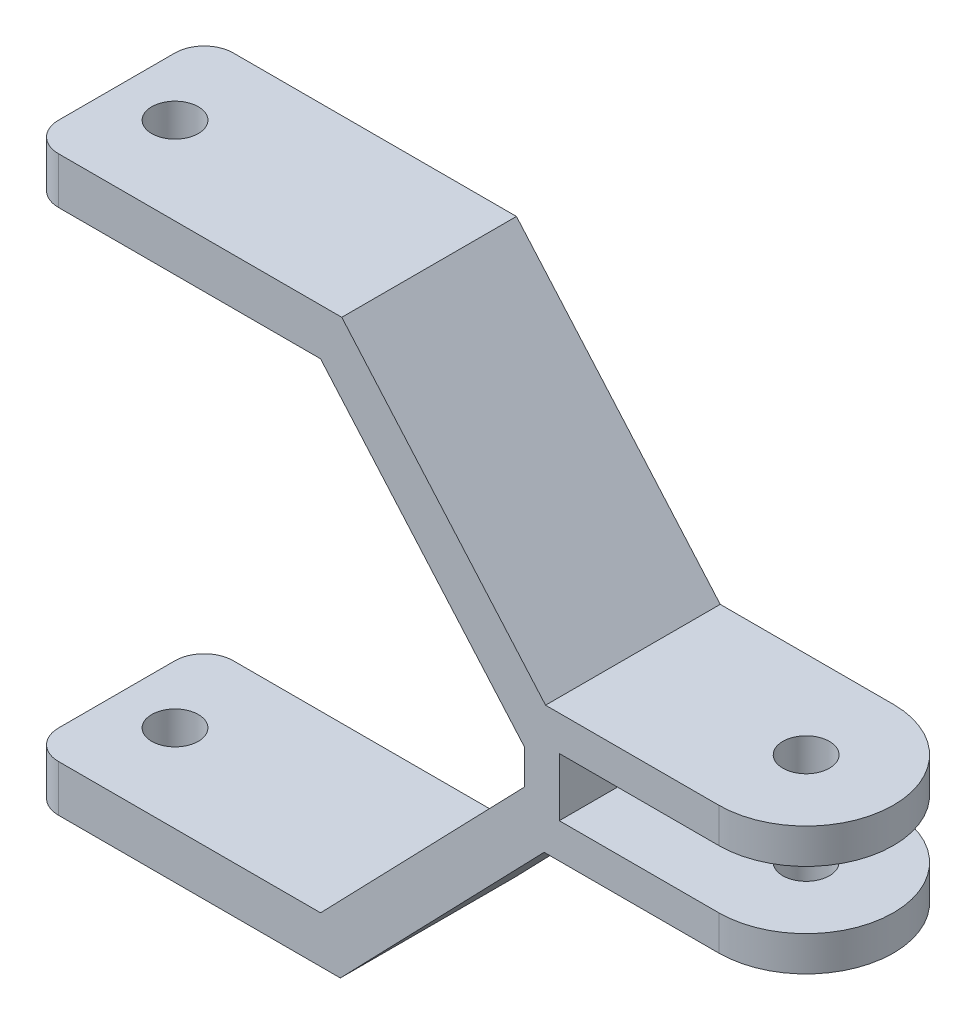
SolidWorks part; units mm, degrees
ref_plane "前基準面" through (0, 0, 0) normal (0, 0, 1) x (1, 0, 0)
ref_plane "上基準面" through (0, 0, 0) normal (0, 1, 0) x (1, 0, 0)
ref_plane "右基準面" through (0, 0, 0) normal (1, 0, 0) x (0, 0, -1)
sketch "草圖1" plane through (0, 0, 0) normal (0, 0, 1) x (1, 0, 0)
  line L0 (-26.6965, 45.2) -> (-47.6965, 45.2)
  line L1 (-25, 0) -> (-51.6965, 0)
  line L2 (7.5, 18.1) -> (7.5, 21.1)
  line L3 (-24.8754, 49.2) -> (-51.6965, 49.2)
  line L4 (-51.6965, 0) -> (-51.6965, 4)
  line L5 (-24.8754, 49.2) -> (-7.3754, 29.1)
  line L6 (-7.5, 18.1) -> (-25, 0)
  line L7 (-7.3754, 29.1) -> (7.5, 29.1)
  line L8 (-7.5, 18.1) -> (7.5, 18.1)
  line L9 (7.5, 26.1) -> (7.5, 29.1)
  line L10 (-26.6965, 4) -> (-47.6965, 4)
  line L11 (-9.1965, 22.1) -> (-26.6965, 4)
  line L12 (-47.6965, 45.2) -> (-51.6965, 45.2)
  line L13 (7.5, 26.1) -> (-6.1965, 26.1)
  line L14 (-51.6965, 4) -> (-47.6965, 4)
  line L15 (-26.6965, 45.2) -> (-9.1965, 25.1)
  line L16 (-9.1965, 25.1) -> (-9.1965, 22.1)
  line L17 (-51.6965, 45.2) -> (-51.6965, 49.2)
  line L18 (-9.1965, 22.1) -> (3.5, 22.1) construction
  line L19 (-9.1965, 25.1) -> (3.5, 25.1) construction
  line L20 (3.5, 22.1) -> (3.5, 25.1) construction
  line L21 (-47.6965, 4) -> (-47.6965, 45.2) construction
  line L22 (-51.6965, 0) -> (-51.6965, 49.2) construction
  line L24 (7.5, 21.1) -> (-6.1965, 21.1)
  line L25 (-6.1965, 26.1) -> (-6.1965, 21.1)
  line L26 (7.5, 18.1) -> (7.5, 29.1) construction
  dimension "D4" = 25
  dimension "D5" = 15
  dimension "D1" = 41.2
  dimension "D2" = 4
  dimension "D3" = 17.5
  dimension "D7" = 3
  dimension "D8" = 3
  dimension "D9" = 3
extrude "填料-伸長1" add sketch "草圖1" along normal blind 15
sketch "草圖2" plane through (0, 0, 0) normal (0, -1, 0) x (1, 0, 0)
  line L0 (-51.6965, 15) -> (-51.6965, 0) construction
  line L1 (-51.6965, 15) -> (-25, 15) construction
  circle A0 centre (-46.6965, 7.5) radius 2
  dimension "D1" = 5
  dimension "D2" = 7.5
  dimension "D3" = 4
extrude "除料-伸長1" cut sketch "草圖2" against normal up to surface (49.2 mm away) up to face at (-38.286, 49.2, 7.5)
sketch "草圖3" plane through (0, 18.1, 0) normal (0, -1, 0) x (1, 0, 0)
  line L0 (7.5, 15) -> (7.5, 0) construction
  circle A0 centre (7.5, 7.5) radius 7.5
extrude "填料-伸長2" add sketch "草圖3" against normal blind 3
sketch "草圖4" plane through (0, 29.1, 0) normal (0, 1, 0) x (1, 0, 0)
  line L0 (7.5, -15) -> (7.5, 0) construction
  circle A0 centre (7.5, -7.5) radius 7.5
  dimension "D1" = 15
extrude "填料-伸長3" add sketch "草圖4" against normal blind 3
sketch "草圖5" plane through (0, 29.1, 0) normal (0, 1, 0) x (1, 0, 0)
  circle A0 centre (7.5, -7.5) radius 2
  dimension "D1" = 4
extrude "除料-伸長2" cut sketch "草圖5" against normal blind 11
fillet "圓角1" radius 2.5 4 edges at (-51.6965, 2, 0) (-51.6965, 47.2, 15) (-51.6965, 47.2, 0) (-51.6965, 2, 15)
